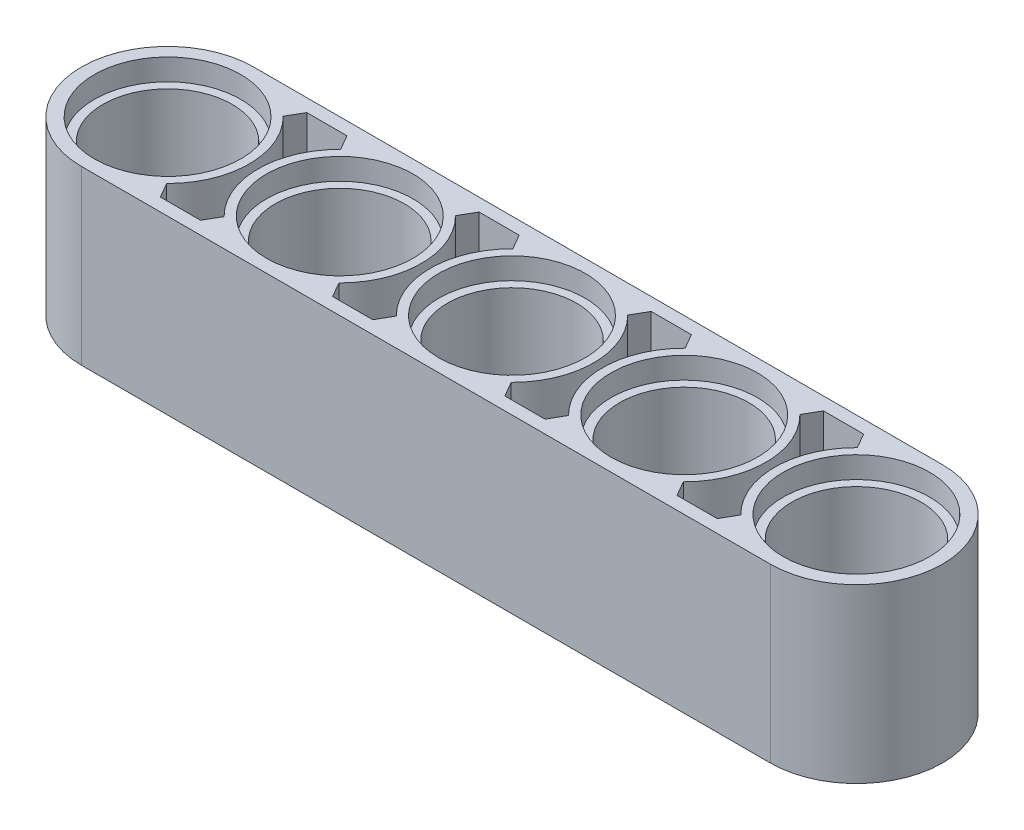
SolidWorks part; units mm, degrees
ref_plane "Front Plane" through (0, 0, 0) normal (0, 0, 1) x (1, 0, 0)
ref_plane "Top Plane" through (0, 0, 0) normal (0, 1, 0) x (1, 0, 0)
ref_plane "Right Plane" through (0, 0, 0) normal (1, 0, 0) x (0, 0, -1)
sketch "Sketch1" plane through (0, 0, 0) normal (0, 1, 0) x (1, 0, 0)
  line L0 (0, 0) -> (32, 0) construction
  line L1 (0, 4) -> (32, 4)
  line L2 (0, -4) -> (32, -4)
  arc A0 (0, 4) -> (0, -4) centre (0, 0) ccw
  arc A1 (32, -4) -> (32, 4) centre (32, 0) ccw
  circle A2 centre (8, 0) radius 3
  circle A3 centre (16, 0) radius 3
  circle A4 centre (0, 0) radius 3
  circle A5 centre (24, 0) radius 3
  circle A6 centre (32, 0) radius 3
  point P2 (-3, 0)
  point P3 (16, 0)
  point P8 (-4, 0)
  point P9 (36, 0)
  point P16 (3, 0)
  point P18 (5, 0)
  point P19 (11, 0)
  point P20 (13, 0)
  point P21 (19, 0)
  point P46 (21, 0)
  point P47 (27, 0)
  point P48 (29, 0)
  point P49 (35, 0)
  point P50 (37, 0)
  dimension "D2" = 20
  dimension "D3" = 6
  dimension "D4" = 6
  dimension "D5" = 6
  dimension "D6" = 4
  dimension "D9" = 6
  dimension "D10" = 6
  dimension "D1" = 40
  dimension "D7" = 1
  dimension "D8" = 2
  dimension "D12" = 2
  dimension "D13" = 2
  dimension "D14" = 2
extrude "Boss-Extrude1" add sketch "Sketch1" along normal blind 8
sketch "Sketch2" plane through (0, 8, 0) normal (0, 1, 0) x (1, 0, 0)
  circle A0 centre (0, 0) radius 3.4
  circle A1 centre (0, 0) radius 3
  dimension "D1" = 6.8
  dimension "D2" = 6
extrude "Cut-Extrude1" cut sketch "Sketch2" against normal blind 1
pattern_linear "LPattern1" count 5 spacing 8 along (1, 0, 0) count 2 spacing 7 along (0, -1, 0) of "Cut-Extrude1"
sketch "Sketch3" plane through (0, 8, 0) normal (0, 1, 0) x (1, 0, 0)
  line L0 (3.0667, -3.4) -> (4.9333, -3.4)
  line L1 (0, -4) -> (32, -4) construction
  line L2 (3.0667, 3.4) -> (4.9333, 3.4)
  line L3 (32, 4) -> (0, 4) construction
  line L4 (3.0667, 3.4) -> (2.6667, 2.7072)
  line L5 (4.9333, 3.4) -> (5.3333, 2.7072)
  line L6 (2.6667, -2.7072) -> (3.0667, -3.4)
  line L7 (5.3333, -2.7072) -> (4.9333, -3.4)
  arc A0 (2.6667, -2.7072) -> (2.6667, 2.7072) centre (0, 0) ccw
  arc A1 (5.3333, 2.7072) -> (5.3333, -2.7072) centre (8, 0) ccw
  dimension "D1" = 7.6
  dimension "D2" = 7.6
  dimension "D3" = 0.6
  dimension "D4" = 0.6
  dimension "D5" = 0.8
  dimension "D6" = 0.8
  dimension "D7" = 120
  dimension "D8" = 120
  dimension "D9" = 120
  dimension "D10" = 120
extrude "Cut-Extrude2" cut sketch "Sketch3" against normal blind 3
pattern_linear "LPattern2" count 4 spacing 8 along (1, 0, 0) count 2 spacing 5 along (0, -1, 0) of "Cut-Extrude2"
